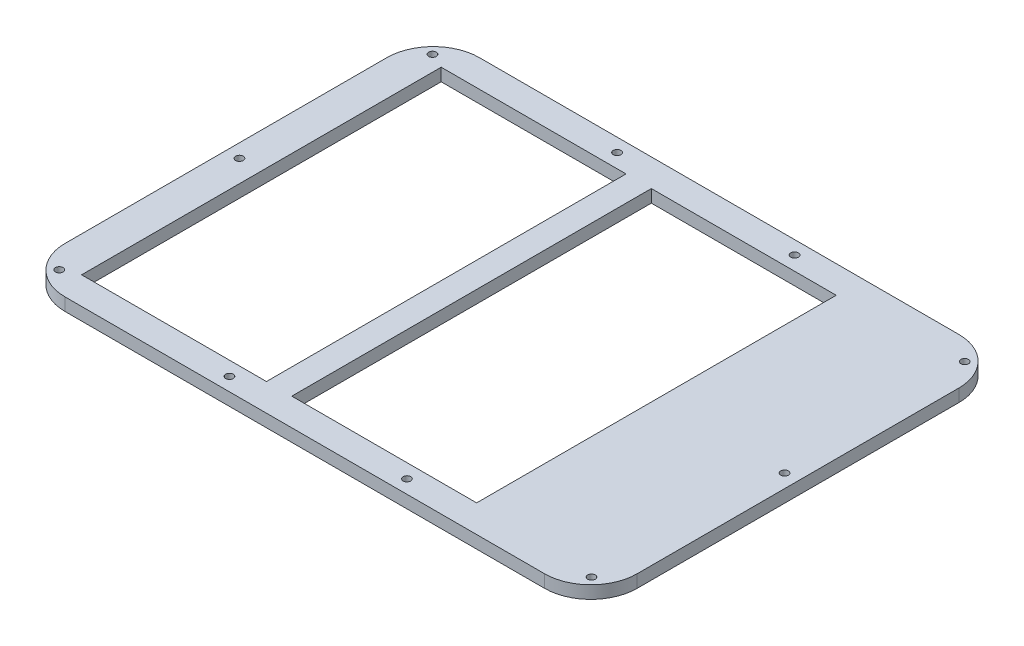
SolidWorks part; units mm, degrees
ref_plane "Plan de face" through (0, 0, 0) normal (0, 0, 1) x (1, 0, 0)
ref_plane "Plan de dessus" through (0, 0, 0) normal (0, 1, 0) x (1, 0, 0)
ref_plane "Plan de droite" through (0, 0, 0) normal (1, 0, 0) x (0, 0, -1)
sketch "Esquisse1" plane through (0, 0, 0) normal (0, 1, 0) x (1, 0, 0)
  line L0 (-112.9703, 81.8261) -> (112.9703, 81.8261)
  line L1 (112.9703, 81.8261) -> (112.9703, -81.8261)
  line L2 (112.9703, -81.8261) -> (-112.9703, -81.8261)
  line L3 (-112.9703, -81.8261) -> (-112.9703, 81.8261)
  line L8 (-98.9703, 71) -> (-25.9703, 71)
  line L9 (-25.9703, 71) -> (-25.9703, -71)
  line L10 (-25.9703, -71) -> (-98.9703, -71)
  line L11 (-98.9703, -71) -> (-98.9703, 71)
  line L12 (-112.9703, 0) -> (112.9703, 0) construction
  line L13 (57.0297, 71) -> (57.0297, -71)
  line L14 (57.0297, -71) -> (-15.9703, -71)
  line L15 (-15.9703, -71) -> (-15.9703, 71)
  line L16 (-15.9703, 71) -> (57.0297, 71)
  line L17 (0, 81.8261) -> (0, -81.8261) construction
  circle A0 centre (-105.0963, 73.6981) radius 1.5
  circle A1 centre (-35.0431, 76.5429) radius 1.5
  circle A5 centre (-107.6363, 0) radius 1.5
  circle A21 centre (107.6363, 0) radius 1.5
  circle A22 centre (35.0431, 76.5429) radius 1.5
  circle A23 centre (105.0963, 73.6981) radius 1.5
  circle A24 centre (105.0963, -73.6981) radius 1.5
  circle A25 centre (35.0431, -76.5429) radius 1.5
  circle A26 centre (-35.0431, -76.5429) radius 1.5
  circle A27 centre (-105.0963, -73.6981) radius 1.5
  point P2 (-107.6363, 0)
  dimension "D1" = 3
  dimension "D8" = 163.6522
  dimension "D14" = 107.6363
  dimension "D12" = 35.0431
  dimension "D11" = 105.0963
  dimension "D2" = 73
  dimension "D3" = 142
  dimension "D4" = 14
  dimension "D6" = 10
  dimension "D7" = 163.6522
  dimension "D9" = 225.9406
  dimension "D10" = 73.6981
  dimension "D13" = 76.5429
  dimension "D5" = 2
extrude "Boss.-Extru.1" add sketch "Esquisse1" along normal blind 5
fillet "Congé2" radius 18.3 4 edges at (112.9703, 2.5, 81.8261) (-112.9703, 2.5, 81.8261) (-112.9703, 2.5, -81.8261) (112.9703, 2.5, -81.8261)
